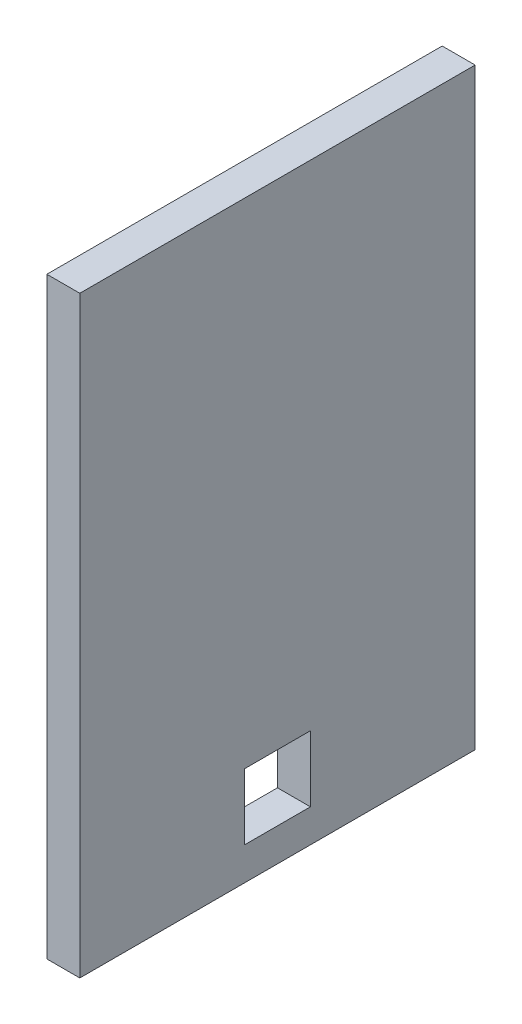
SolidWorks part; units mm, degrees
material "Pino"
ref_plane "Alzado" through (0, 0, 0) normal (0, 0, 1) x (1, 0, 0)
ref_plane "Planta" through (0, 0, 0) normal (0, 1, 0) x (1, 0, 0)
ref_plane "Vista lateral" through (0, 0, 0) normal (1, 0, 0) x (0, 0, -1)
sketch "Croquis1" plane through (0, 0, 0) normal (1, 0, 0) x (0, 0, -1)
  line L1 (-152.4, 0) -> (152.4, 0)
  line L2 (-152.4, 0) -> (-152.4, 304.8)
  line L3 (-152.4, 304.8) -> (152.4, 304.8)
  line L4 (152.4, 0) -> (152.4, 304.8)
  point P4 (0, 0)
  dimension "D1" = 304.8
  dimension "D2" = 304.8
extrude "Saliente-Extruir1" add sketch "Croquis1" against normal blind 25.4
sketch "Croquis3" plane through (0, 0, 0) normal (1, 0, 0) x (0, 0, -1)
  line L0 (-152.4, 0) -> (152.4, 0) construction
  line L1 (-25.4, 25.4) -> (25.4, 25.4)
  line L2 (-25.4, 25.4) -> (-25.4, 76.2)
  line L3 (-25.4, 76.2) -> (25.4, 76.2)
  line L4 (25.4, 25.4) -> (25.4, 76.2)
  line L5 (-25.4, 25.4) -> (25.4, 76.2) construction
  line L6 (-25.4, 76.2) -> (25.4, 25.4) construction
  point P0 (0, 50.8)
  dimension "D1" = 50.8
  dimension "D2" = 50.8
  dimension "D3" = 25.4
extrude "Cortar-Extruir2" cut sketch "Croquis3" against normal up to surface (25.4 mm away) up to face at (-25.4, 152.4, 0)
sketch "Sketch1" plane through (0, 304.8, 0) normal (0, 1, 0) x (1, 0, 0)
  line L1 (0, 152.4) -> (-25.4, 152.4)
  line L2 (0, 152.4) -> (0, -152.4)
  line L3 (0, -152.4) -> (-25.4, -152.4)
  line L4 (-25.4, 152.4) -> (-25.4, -152.4)
extrude "Boss-Extrude1" add sketch "Sketch1" along normal blind 152.4
